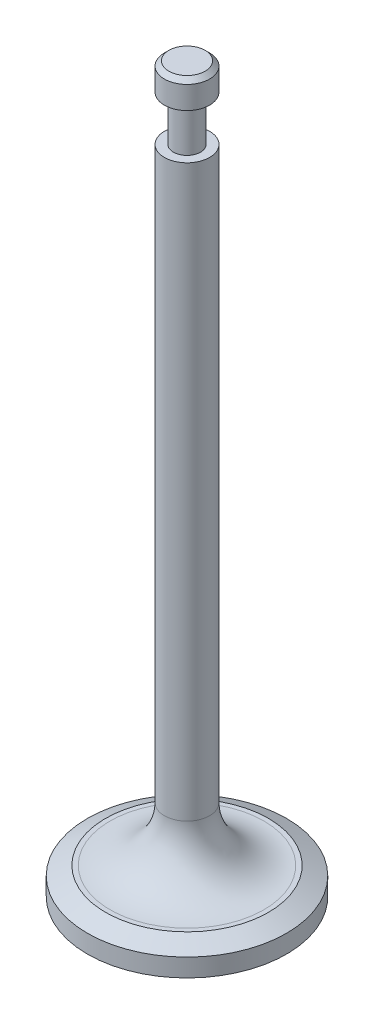
SolidWorks part; units mm, degrees
ref_plane "Front Plane" through (0, 0, 0) normal (0, 0, 1) x (1, 0, 0)
ref_plane "Top Plane" through (0, 0, 0) normal (0, 1, 0) x (1, 0, 0)
ref_plane "Right Plane" through (0, 0, 0) normal (1, 0, 0) x (0, 0, -1)
sketch "Sketch1" plane through (0, 0, 0) normal (1, 0, 0) x (0, 0, -1)
  line L0 (0, 0) -> (0, -80)
  line L1 (0, -80) -> (11, -80)
  line L2 (11, -80) -> (11, -77)
  line L3 (11, -77) -> (2.5, -77)
  line L4 (2.5, -77) -> (2.5, -8)
  line L5 (2.5, -8) -> (1.5, -8)
  line L6 (1.5, -8) -> (1.5, -3)
  line L7 (1.5, -3) -> (2.5, -3)
  line L8 (2.5, -3) -> (2.5, 0)
  line L9 (2.5, 0) -> (0, 0)
  dimension "D1" = 80
  dimension "D2" = 11
  dimension "D3" = 3
  dimension "D4" = 2.5
  dimension "D5" = 3
  dimension "D6" = 5
  dimension "D7" = 1
  dimension "D8" = 2.5
  dimension "D9" = 1
revolve "Revolve1" add sketch "Sketch1" angle 360 about L0
fillet "Fillet1" radius 6 1 edges at (0, -77, 2.5)
chamfer "Chamfer1" distance 1 distance2 2 1 edges at (0, -77, 11)
chamfer "Chamfer2" distance 0.5 angle 45 1 edges at (0, 0, 2.5)
